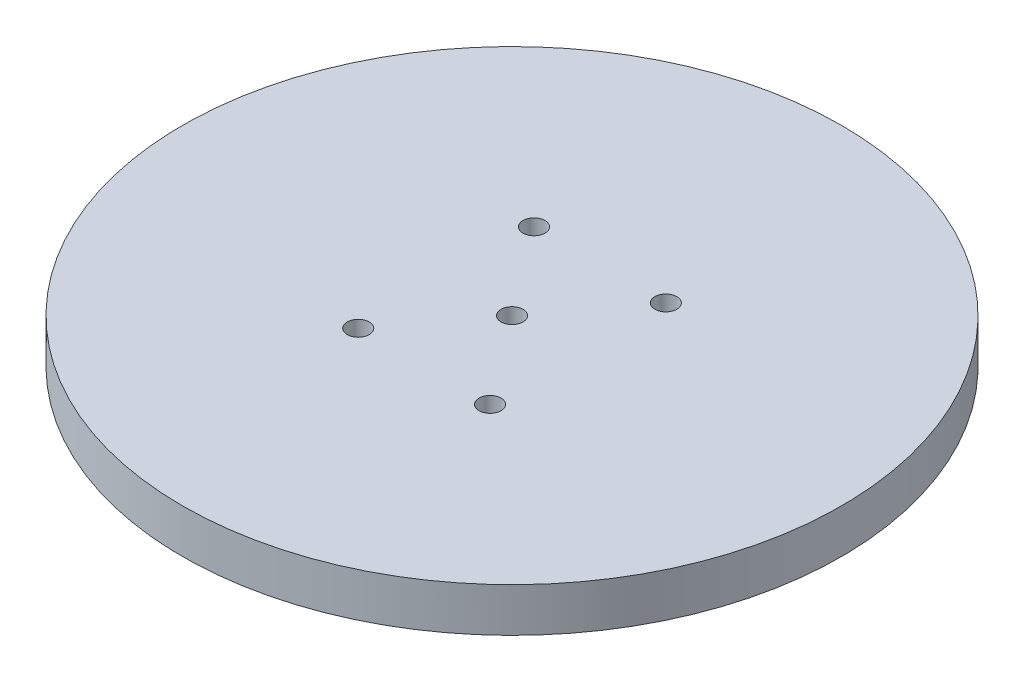
SolidWorks part; units mm, degrees
ref_plane "Front Plane" through (0, 0, 0) normal (0, 0, 1) x (1, 0, 0)
ref_plane "Top Plane" through (0, 0, 0) normal (0, 1, 0) x (1, 0, 0)
ref_plane "Right Plane" through (0, 0, 0) normal (1, 0, 0) x (0, 0, -1)
sketch "Sketch1" plane through (0, 0, 0) normal (0, 1, 0) x (1, 0, 0)
  circle A0 centre (0, 0) radius 75
  dimension "D1" = 150
extrude "Boss-Extrude1" add sketch "Sketch1" along normal blind 30
sketch "Sketch2" plane through (0, 0, 0) normal (0, -1, 0) x (1, 0, 0)
  circle A0 centre (0, 0) radius 75
  circle A1 centre (0, 0) radius 7.5
  dimension "D1" = 15
  dimension "D2" = 150
extrude "Cut-Extrude1" cut sketch "Sketch2" against normal blind 20
sketch "Sketch3" plane through (0, 30, 0) normal (0, 1, 0) x (1, 0, 0)
  circle A0 centre (0, 0) radius 2.5
  dimension "D1" = 5
extrude "Cut-Extrude2" cut sketch "Sketch3" against normal blind 30
sketch "Sketch4" plane through (0, 30, 0) normal (0, 1, 0) x (1, 0, 0)
  line L1 (-15, 20) -> (15, 20)
  line L2 (-15, 20) -> (-15, -20)
  line L3 (-15, -20) -> (15, -20)
  line L4 (15, 20) -> (15, -20)
  line L5 (-15, 20) -> (15, -20) construction
  line L6 (-15, -20) -> (15, 20) construction
  circle A0 centre (-15, 20) radius 2.5
  circle A1 centre (15, 20) radius 2.5
  circle A2 centre (-15, -20) radius 2.5
  circle A3 centre (15, -20) radius 2.5
  point P0 (0, 0)
  dimension "D3" = 5
  dimension "D1" = 40
  dimension "D2" = 30
extrude "Cut-Extrude3" cut sketch "Sketch4" against normal blind 10 contours A0 | A1 | A2 | A3
